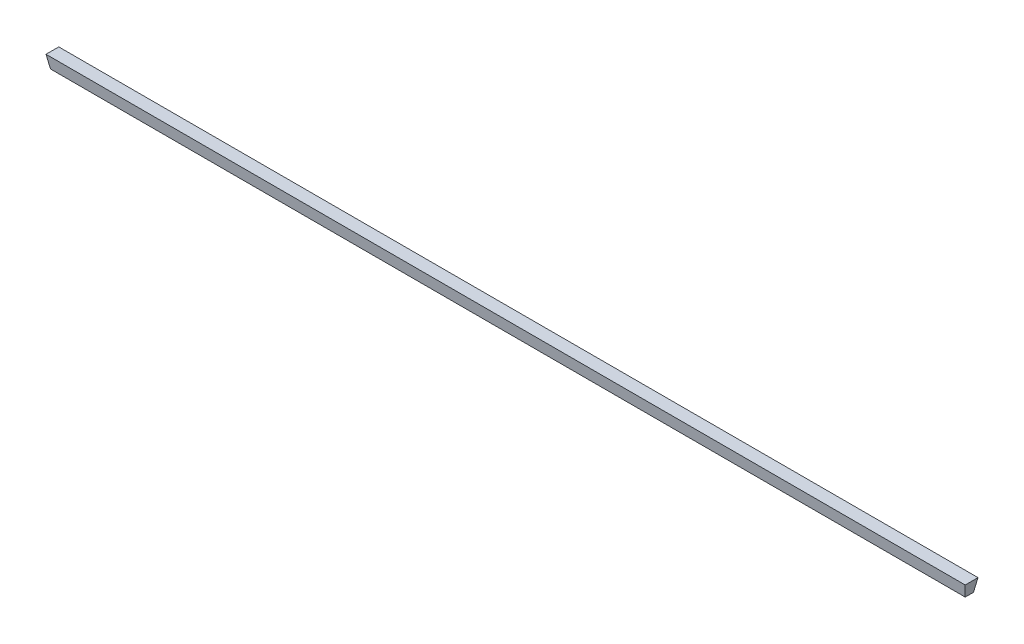
SolidWorks part; units mm, degrees
ref_plane "Front Plane" through (0, 0, 0) normal (0, 0, 1) x (1, 0, 0)
ref_plane "Top Plane" through (0, 0, 0) normal (0, 1, 0) x (1, 0, 0)
ref_plane "Right Plane" through (0, 0, 0) normal (1, 0, 0) x (0, 0, -1)
sketch "Sketch1" plane through (0, 0, 0) normal (0, 1, 0) x (1, 0, 0)
  line L1 (-1828.8, 25.4) -> (1828.8, 25.4)
  line L2 (-1828.8, 25.4) -> (-1828.8, -25.4)
  line L3 (-1828.8, -25.4) -> (1828.8, -25.4)
  line L4 (1828.8, 25.4) -> (1828.8, -25.4)
  line L5 (-1828.8, 25.4) -> (1828.8, -25.4) construction
  line L6 (-1828.8, -25.4) -> (1828.8, 25.4) construction
  point P0 (0, 0)
  dimension "D1" = 3657.6
  dimension "D2" = 50.8
extrude "Boss-Extrude1" add sketch "Sketch1" against normal blind 50.8 draft 10
